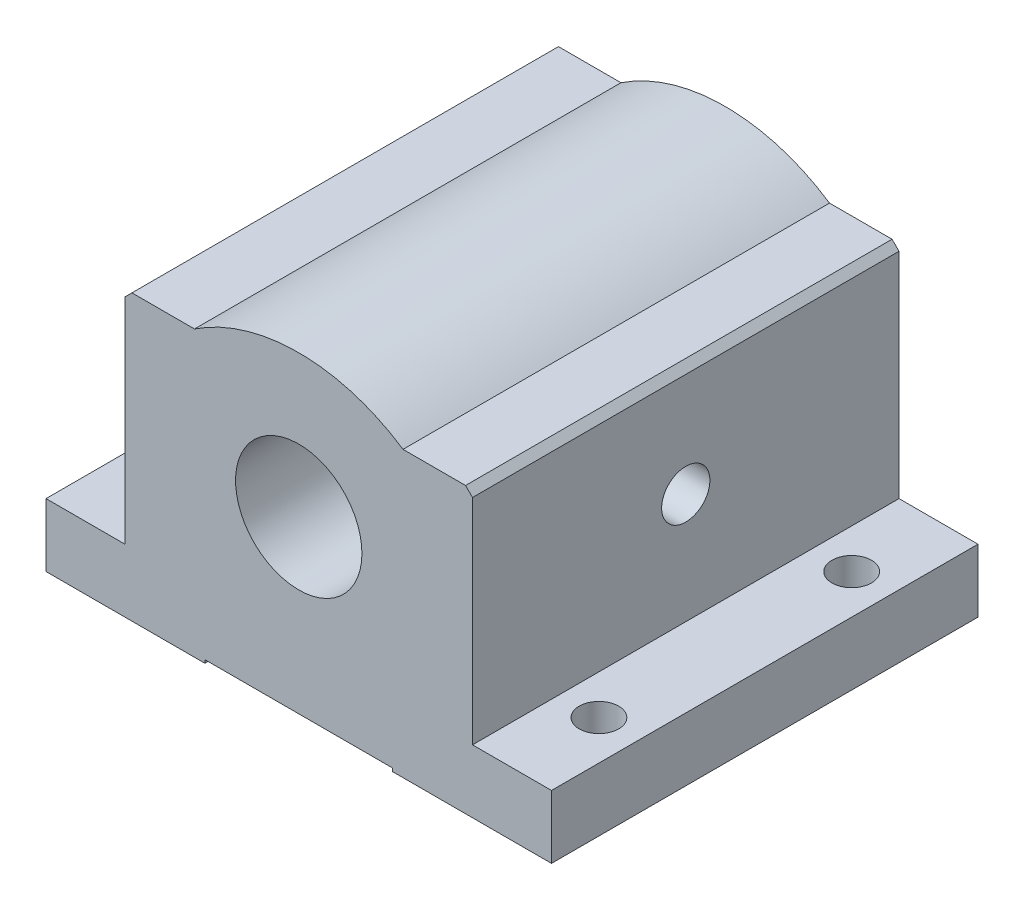
SolidWorks part; units mm, degrees
ref_plane "Front Plane" through (0, 0, 0) normal (0, 0, 1) x (1, 0, 0)
ref_plane "Top Plane" through (0, 0, 0) normal (0, 1, 0) x (1, 0, 0)
ref_plane "Right Plane" through (0, 0, 0) normal (1, 0, 0) x (0, 0, -1)
sketch "Sketch1" plane through (0, 0, 0) normal (0, 0, 1) x (1, 0, 0)
  line L0 (-25.4, -9.525) -> (-17.4625, -9.525)
  line L1 (-25.4, 15.875) -> (25.4, 15.875)
  line L2 (-25.4, 15.875) -> (-25.4, -15.875)
  line L3 (-25.4, -15.875) -> (25.4, -15.875)
  line L4 (25.4, 15.875) -> (25.4, -15.875)
  line L5 (-17.4625, -9.525) -> (-17.4625, 12.7)
  line L6 (-17.4625, 12.7) -> (17.4625, 12.7)
  line L7 (17.4625, 12.7) -> (17.4625, -9.525)
  line L8 (17.4625, -9.525) -> (25.4, -9.525)
  line L9 (0, 1.5748) -> (0, -15.875) construction
  circle A0 centre (0, 1.5748) radius 6.35
  point P4 (25.4, 0)
  point P5 (0, 15.875)
  dimension "ID | For Bearing OD" = 12.7
  dimension "Overall Height" = 31.75
  dimension "Overall Width" = 50.8
  dimension "Base Thickness" = 6.35
  dimension "K" = 28.575
  dimension "G" = 34.925
  dimension "Center Height" = 17.4498
sketch "Sketch2" plane through (0, 0, 0) normal (1, 0, 0) x (0, 0, -1)
  line L0 (-21.4312, 0) -> (21.4312, 0) construction
  line L2 (0, 15.875) -> (0, -15.875) construction
  line L3 (0, 15.875) -> (0, -15.875) construction
  circle A0 centre (0, 1.5748) radius 2.4257
  point P2 (0, 0)
  point P11 (-15.875, 0)
  dimension "Grease Hole Diameter" = 4.8514
  dimension "Overall Length" = 42.8625
  dimension "For Maximum Bearing Length" = 31.75
sketch "Sketch3" plane through (0, 0, 0) normal (0, 1, 0) x (1, 0, 0)
  line L1 (-25.4, 21.4312) -> (25.4, 21.4313)
  line L2 (-25.4, 21.4312) -> (-25.4, -21.4313)
  line L3 (-25.4, -21.4313) -> (25.4, -21.4313)
  line L4 (25.4, 21.4313) -> (25.4, -21.4313)
  line L5 (-21.4376, 12.7) -> (21.4376, 12.7) construction
  line L6 (-21.4376, 12.7) -> (-21.4376, -12.7) construction
  line L7 (-21.4376, -12.7) -> (21.4376, -12.7) construction
  line L8 (21.4376, 12.7) -> (21.4376, -12.7) construction
  circle A0 centre (-21.4376, 12.7) radius 1.9844
  point P4 (0, 21.4312)
  point P5 (25.4, 0)
  point P12 (0, 12.7)
  point P13 (21.4376, 0)
  dimension "Mounting Hole Diameter" = 3.9688
  dimension "Mounting Hole Center to Center, Length" = 25.4
  dimension "Mounting Hole Center to Center, Width" = 42.8752
sketch "Sketch4" plane through (0, 0, 0) normal (0, 0, 1) x (1, 0, 0)
  line L0 (-25.4, -9.525) -> (-17.4625, -9.525) construction
  line L1 (-25.4, -9.525) -> (-17.4625, -9.525)
  line L2 (-25.4, -15.875) -> (25.4, -15.875) construction
  line L3 (17.4625, -9.525) -> (25.4, -9.525) construction
  line L4 (17.4625, 12.7) -> (17.4625, -9.525) construction
  line L5 (-17.4625, 12.7) -> (17.4625, 12.7) construction
  line L6 (-17.4625, -9.525) -> (-17.4625, 12.7) construction
  line L7 (-25.4, -15.875) -> (-9.4298, -15.875)
  line L8 (17.4625, -9.525) -> (25.4, -9.525)
  line L9 (17.4625, 12.7) -> (17.4625, -9.525)
  line L10 (-17.4625, 12.7) -> (-10.4775, 12.7)
  line L11 (-17.4625, -9.525) -> (-17.4625, 12.7)
  line L12 (-25.4, -9.525) -> (-25.4, -15.875)
  line L13 (25.4, -9.525) -> (25.4, -15.875)
  line L14 (10.4775, 12.7) -> (17.4625, 12.7)
  line L15 (-25.4, 15.875) -> (25.4, 15.875) construction
  line L16 (-9.4298, -15.875) -> (-9.4297, -15.5575)
  line L17 (-9.4297, -15.5575) -> (9.4297, -15.5575)
  line L18 (9.4297, -15.5575) -> (9.4298, -15.875)
  line L19 (0, 1.5748) -> (0, -15.875) construction
  line L22 (9.4298, -15.875) -> (25.4, -15.875)
  circle A0 centre (0, 1.5748) radius 6.35 construction
  circle A1 centre (0, 1.5748) radius 6.35
  arc A2 (-10.4775, 12.7) -> (10.4775, 12.7) centre (0, -3.0004) cw
  point P14 (0, 15.875)
  point P17 (0, 15.875)
  point P20 (0, -15.5575)
  dimension "D1" = 20.955
  dimension "D2" = 18.8595
  dimension "D3" = 0.3175
extrude "Boss-Extrude1" add sketch "Sketch4" along normal up to vertex (21.4312 mm away) from vertex at -21.4312 starting at point (0, 0, -21.4312)
sketch "Sketch5" plane through (0, -9.525, 0) normal (0, 1, 0) x (1, 0, 0)
  circle A0 centre (-21.4376, 12.7) radius 1.9844 construction
  circle A1 centre (-21.4376, 12.7) radius 1.9844
  circle A2 centre (21.4376, 12.7) radius 1.9844
  circle A3 centre (21.4376, -12.7) radius 1.9844
  circle A4 centre (-21.4376, -12.7) radius 1.9844
extrude "Cut-Extrude1" cut sketch "Sketch5" against normal through all
chamfer "Chamfer1" distance 0.6985 angle 45 2 edges at (-17.4625, 12.7, 0) (17.4625, 12.7, 0)
ref_plane "Plane1" through (0, 0, 15.875) normal (0, 0, 1) x (1, 0, 0)
sketch "Sketch7" plane through (17.4625, 0, 0) normal (1, 0, 0) x (0, 0, -1)
  circle A0 centre (0, 1.5748) radius 2.4257 construction
  circle A1 centre (0, 1.5748) radius 2.4257
extrude "Cut-Extrude3" cut sketch "Sketch7" against normal up to next
equation "\"D1@Sketch4\"=0.6*\"G@Sketch1\""
equation "\"D2@Sketch4\"=\"D1@Sketch4\"*.9"
equation "\"D1@Chamfer1\"=.02*\"G@Sketch1\""
equation "\"D3@Sketch4\"=.05*\"Base Thickness@Sketch1\""
